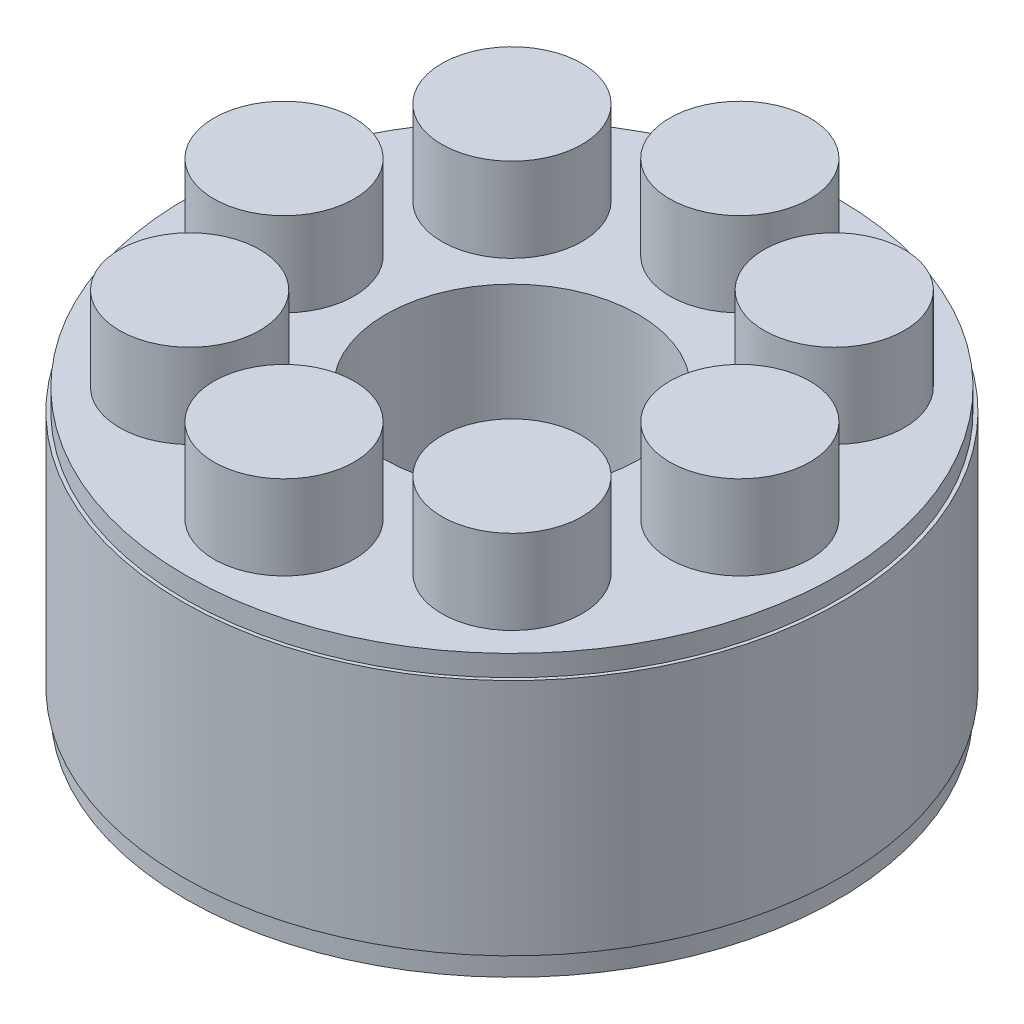
SolidWorks part; units mm, degrees
ref_plane "前视基准面" through (0, 0, 0) normal (0, 0, 1) x (1, 0, 0)
ref_plane "上视基准面" through (0, 0, 0) normal (0, 1, 0) x (1, 0, 0)
ref_plane "右视基准面" through (0, 0, 0) normal (1, 0, 0) x (0, 0, -1)
other "Configuration Table"
sketch "草图1" plane through (0, 0, 0) normal (0, 1, 0) x (1, 0, 0)
  circle A0 centre (0, 0) radius 23.25
  circle A1 centre (0, 0) radius 9
  dimension "D1" = 18
  dimension "D2" = 46.5
extrude "凸台-拉伸1" add sketch "草图1" along normal mid plane 20
sketch "草图2" plane through (0, 10, 0) normal (0, 1, 0) x (1, 0, 0)
  line L0 (0, 0) -> (16.25, 0) construction
  circle A0 centre (0, 0) radius 16.25 construction
  circle A1 centre (16.25, 0) radius 5
  dimension "D1" = 32.5
  dimension "D2" = 10
extrude "凸台-拉伸2" add sketch "草图2" along normal blind 6
pattern_circular "阵列(圆周)1" count 8 over 360 about axis through (0, 0, 0) along (0, 1, 0) of "凸台-拉伸2"
sketch "草图4" plane through (0, 0, 0) normal (0, 1, 0) x (1, 0, 0)
  circle A0 centre (0, 0) radius 23.5
  circle A1 centre (0, 0) radius 9 construction
  circle A2 centre (0, 0) radius 9
  dimension "D1" = 47
extrude "凸台-拉伸3" add sketch "草图4" along normal mid plane 17
